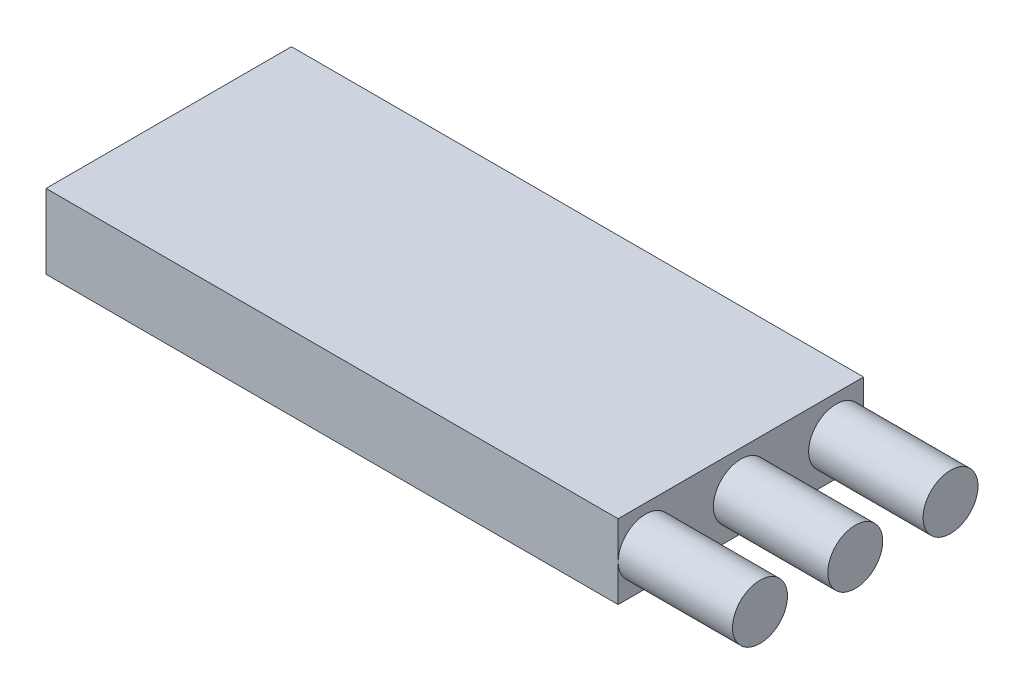
SolidWorks part; units mm, degrees
ref_plane "Front Plane" through (0, 0, 0) normal (0, 0, 1) x (1, 0, 0)
ref_plane "Top Plane" through (0, 0, 0) normal (0, 1, 0) x (1, 0, 0)
ref_plane "Right Plane" through (0, 0, 0) normal (1, 0, 0) x (0, 0, -1)
sketch "Sketch1" plane through (0, 0, 0) normal (0, 1, 0) x (1, 0, 0)
  line L1 (0, 0) -> (50, 0)
  line L2 (0, 0) -> (0, 21.45)
  line L3 (0, 21.45) -> (50, 21.45)
  line L4 (50, 0) -> (50, 21.45)
  dimension "D1" = 21.45
  dimension "D2" = 50
extrude "Boss-Extrude1" add sketch "Sketch1" along normal blind 6.5
sketch "Sketch2" plane through (50, 0, 0) normal (1, 0, 0) x (0, 0, -1)
  line L0 (0, 3.25) -> (21.45, 3.25) construction
  line L1 (0, 6.5) -> (0, 0) construction
  line L2 (21.45, 6.5) -> (21.45, 0) construction
  circle A0 centre (10.725, 3.25) radius 2.4
  circle A1 centre (2.4, 3.25) radius 2.4
  circle A2 centre (19.05, 3.25) radius 2.4
  dimension "D1" = 4.8
extrude "Boss-Extrude2" add sketch "Sketch2" along normal blind 10
